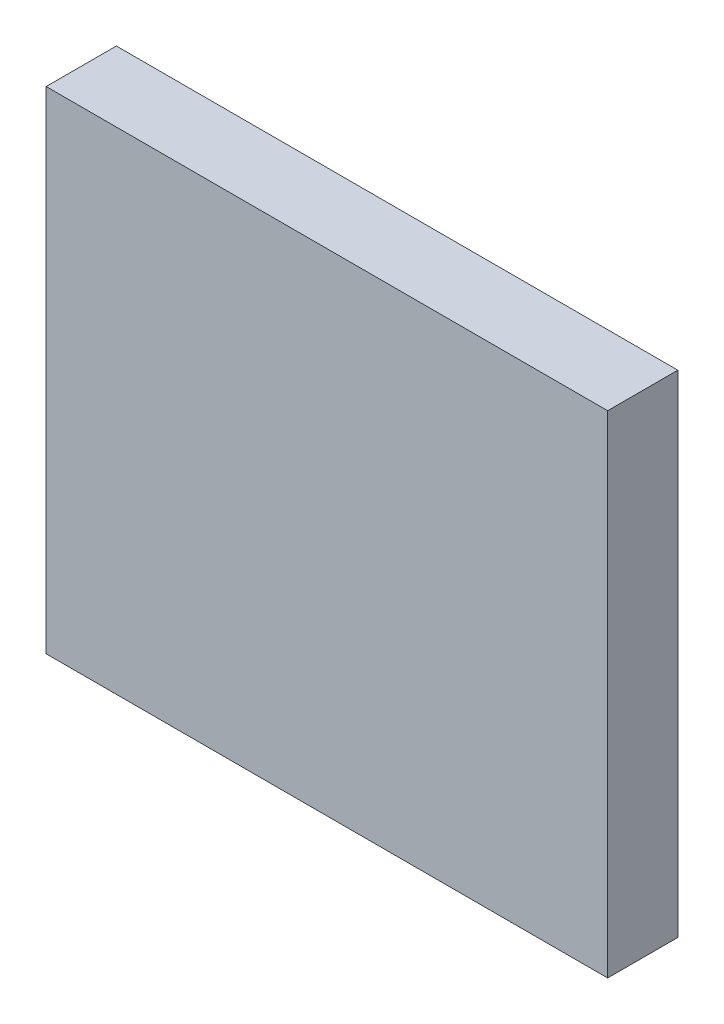
SolidWorks part; units mm, degrees
ref_plane "Plan de face" through (0, 0, 0) normal (0, 0, 1) x (1, 0, 0)
ref_plane "Plan de dessus" through (0, 0, 0) normal (0, 1, 0) x (1, 0, 0)
ref_plane "Plan de droite" through (0, 0, 0) normal (1, 0, 0) x (0, 0, -1)
sketch "Esquisse1" plane through (0, 0, 0) normal (0, 0, 1) x (1, 0, 0)
  line L1 (0, 0) -> (40, 0)
  line L2 (0, 0) -> (0, 35)
  line L3 (0, 35) -> (40, 35)
  line L4 (40, 0) -> (40, 35)
  dimension "D1" = 40
  dimension "D2" = 35
extrude "Boss.-Extru.1" add sketch "Esquisse1" along normal blind 5
